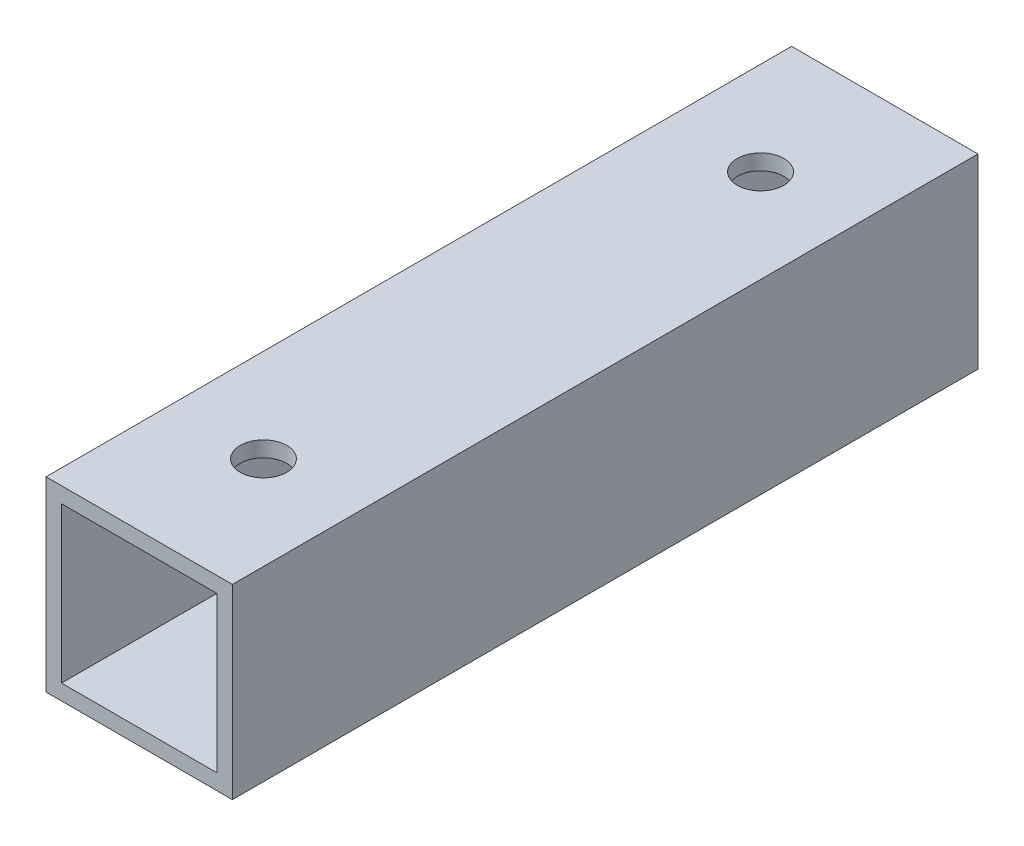
SolidWorks part; units mm, degrees
material "6061 Alloy"
ref_plane "Front Plane" through (0, 0, 0) normal (0, 0, 1) x (1, 0, 0)
ref_plane "Top Plane" through (0, 0, 0) normal (0, 1, 0) x (1, 0, 0)
ref_plane "Right Plane" through (0, 0, 0) normal (1, 0, 0) x (0, 0, -1)
sketch "Sketch1" plane through (0, 0, 0) normal (0, 0, 1) x (1, 0, 0)
  line L1 (-9.525, -9.525) -> (9.525, -9.525)
  line L2 (-9.525, -9.525) -> (-9.525, 9.525)
  line L3 (-9.525, 9.525) -> (9.525, 9.525)
  line L4 (9.525, -9.525) -> (9.525, 9.525)
  line L5 (-9.525, -9.525) -> (9.525, 9.525) construction
  line L6 (-9.525, 9.525) -> (9.525, -9.525) construction
  line L7 (-7.9375, -7.9375) -> (7.9375, -7.9375)
  line L8 (-7.9375, -7.9375) -> (-7.9375, 7.9375)
  line L9 (-7.9375, 7.9375) -> (7.9375, 7.9375)
  line L10 (7.9375, -7.9375) -> (7.9375, 7.9375)
  line L11 (-7.9375, -7.9375) -> (7.9375, 7.9375) construction
  line L12 (-7.9375, 7.9375) -> (7.9375, -7.9375) construction
  point P0 (0, 0)
  point P6 (0, 0)
  dimension "D1" = 19.05
  dimension "D2" = 19.05
  dimension "D3" = 1.5875
  dimension "D4" = 1.5875
extrude "Boss-Extrude1" add sketch "Sketch1" along normal blind 76.2
sketch "Sketch2" plane through (0, 0, 0) normal (0, 1, 0) x (1, 0, 0)
  line L0 (0, 0) -> (0, -12.7) construction
  line L1 (0, -76.2) -> (0, -63.5) construction
  line L2 (9.525, -76.2) -> (-9.525, -76.2) construction
  circle A0 centre (0, -12.7) radius 2.3813
  circle A1 centre (0, -63.5) radius 2.3812
extrude "Cut-Extrude1" cut sketch "Sketch2" against normal through all both and the other way through all
sketch "Sketch3" plane through (-9.525, 0, 0) normal (-1, 0, 0) x (0, 0, 1)
  line L0 (0, 0) -> (38.1, 0) construction
  line L1 (0, 9.525) -> (0, -9.525) construction
  circle A0 centre (38.1, 0) radius 3.9687
extrude "Cut-Extrude2" cut sketch "Sketch3" against normal up to next
